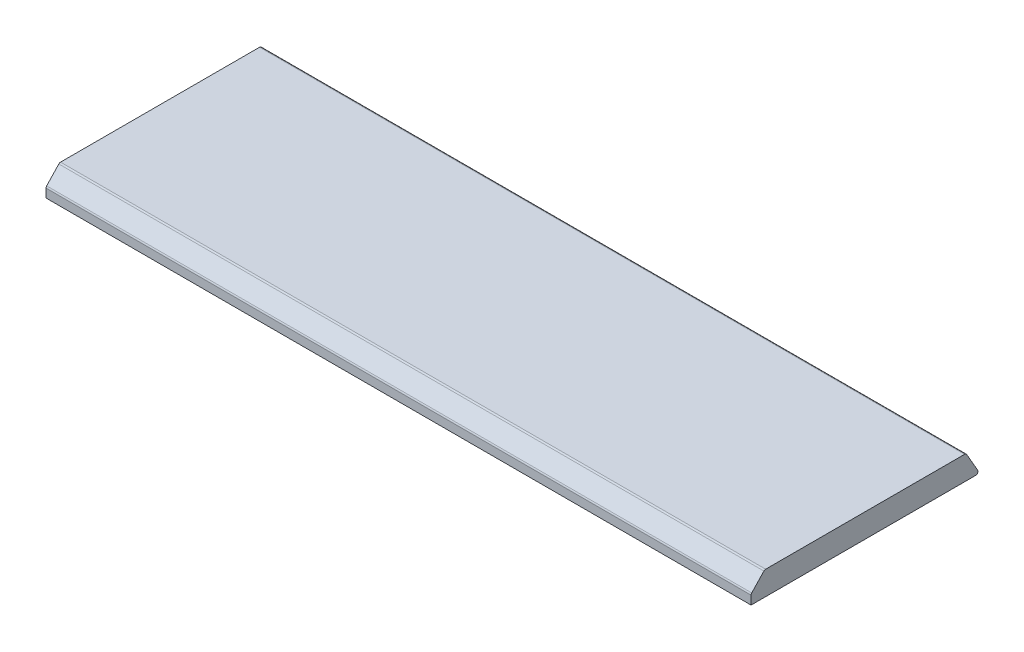
SolidWorks part; units mm, degrees
ref_plane "Front Plane" through (0, 0, 0) normal (0, 0, 1) x (1, 0, 0)
ref_plane "Top Plane" through (0, 0, 0) normal (0, 1, 0) x (1, 0, 0)
ref_plane "Right Plane" through (0, 0, 0) normal (1, 0, 0) x (0, 0, -1)
sketch "Sketch1" plane through (0, 0, 0) normal (1, 0, 0) x (0, 0, -1)
  line L0 (0, 0) -> (76.2, 0)
  line L5 (76.2, 0) -> (71.6173, 7.9375)
  line L6 (71.6173, 7.9375) -> (4.506, 7.9375)
  line L7 (4.506, 7.9375) -> (0, 3.175)
  line L8 (0, 3.175) -> (0, 0)
  line L9 (-1.3703, 1.7267) -> (-22.7974, -20.92) construction
  line L10 (72.5391, 6.3408) -> (75.5126, 1.1906) construction
  dimension "D1" = 7.9375
extrude "Boss-Extrude1" add sketch "Sketch1" against normal blind 234.95
ref_plane "Plane1" through (-117.475, 0, 0) normal (1, 0, 0) x (0, 0, -1)
fillet "Fillet1" radius 0.7937 4 edges at (-117.475, 7.9375, -71.6173) (-117.475, 0, -76.2) (-117.475, 3.175, 0) (-117.475, 7.9375, -4.506)
